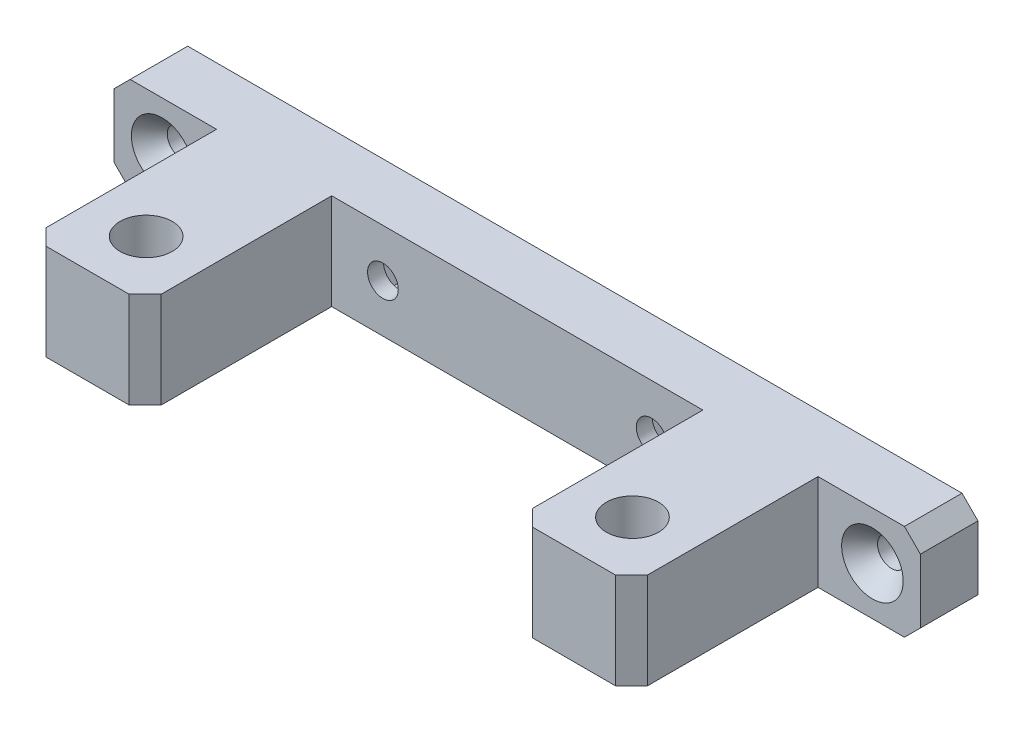
SolidWorks part; units mm, degrees
ref_plane "Front Plane" through (0, 0, 0) normal (0, 0, 1) x (1, 0, 0)
ref_plane "Top Plane" through (0, 0, 0) normal (0, 1, 0) x (1, 0, 0)
ref_plane "Right Plane" through (0, 0, 0) normal (1, 0, 0) x (0, 0, -1)
sketch "Sketch1" plane through (0, 0, 0) normal (0, 0, 1) x (1, 0, 0)
  line L0 (63, 0) -> (63, -15) construction
  line L1 (0, 0) -> (126, 0)
  line L2 (0, 0) -> (0, -15)
  line L3 (0, -15) -> (126, -15)
  line L4 (126, 0) -> (126, -15)
  line L5 (63, -7.5) -> (42, -7.5) construction
  line L6 (42, -7.5) -> (7.5, -7.5) construction
  circle A0 centre (42, -7.5) radius 2.4
  circle A1 centre (7.5, -7.5) radius 2.2
  circle A2 centre (118.5, -7.5) radius 2.2
  circle A3 centre (84, -7.5) radius 2.4
  dimension "D4" = 4.8
  dimension "D6" = 4.4
  dimension "D1" = 15
  dimension "D2" = 126
  dimension "D3" = 21
  dimension "D5" = 34.5
extrude "Boss-Extrude1" add sketch "Sketch1" along normal blind 9
sketch "Sketch2" plane through (0, 0, 9) normal (0, 0, 1) x (1, 0, 0)
  line L0 (63, 0) -> (63, -15) construction
  line L1 (126, 0) -> (0, 0) construction
  line L2 (0, -15) -> (126, -15) construction
  line L3 (63, -7.5) -> (25, -7.5) construction
  line L4 (110, -15) -> (92, -15)
  line L5 (16, 0) -> (34, 0)
  line L6 (16, 0) -> (16, -15)
  line L7 (16, -15) -> (34, -15)
  line L8 (34, 0) -> (34, -15)
  line L9 (16, 0) -> (34, -15) construction
  line L10 (16, -15) -> (34, 0) construction
  line L11 (92, 0) -> (92, -15)
  line L12 (110, 0) -> (92, 0)
  line L13 (110, 0) -> (110, -15)
  dimension "D1" = 29
  dimension "D2" = 18
extrude "Boss-Extrude2" add sketch "Sketch2" along normal blind 29.15
sketch "Sketch4" plane through (0, -15, 0) normal (0, -1, 0) x (1, 0, 0)
  line L0 (16, 9) -> (34, 9) construction
  line L1 (25, 9) -> (25, 29) construction
  line L2 (63, 9) -> (63, 0) construction
  line L3 (34, 9) -> (92, 9) construction
  line L4 (0, 0) -> (126, 0) construction
  line L5 (63, 9) -> (63, 24) construction
  line L6 (63, 24) -> (63, 40) construction
  line L7 (25, 29) -> (25, 40) construction
  circle A0 centre (25, 29) radius 4.075
  circle A1 centre (101, 29) radius 4.075
  dimension "D1" = 8.15
  dimension "D3" = 15
  dimension "D4" = 16
  dimension "D5" = 11
extrude "Cut-Extrude1" cut sketch "Sketch4" against normal through all both and the other way through all
sketch "Sketch5" plane through (0, 0, 0) normal (0, 0, -1) x (-1, 0, 0)
  line L0 (-63, 0) -> (-63, -15) construction
  line L1 (-81.8927, -11.15) -> (-79.7853, -7.5)
  line L2 (-79.7853, -7.5) -> (-81.8927, -3.85)
  line L3 (-81.8927, -3.85) -> (-86.1073, -3.85)
  line L4 (-86.1073, -3.85) -> (-88.2147, -7.5)
  line L5 (-88.2147, -7.5) -> (-86.1073, -11.15)
  line L6 (-86.1073, -11.15) -> (-81.8927, -11.15)
  line L7 (-126, 0) -> (0, 0) construction
  line L8 (0, -15) -> (-126, -15) construction
  line L9 (-39.8927, -11.15) -> (-44.1073, -11.15)
  line L10 (-37.7853, -7.5) -> (-39.8927, -11.15)
  line L11 (-39.8927, -3.85) -> (-37.7853, -7.5)
  line L12 (-44.1073, -3.85) -> (-39.8927, -3.85)
  line L13 (-46.2147, -7.5) -> (-44.1073, -3.85)
  line L14 (-44.1073, -11.15) -> (-46.2147, -7.5)
  circle A0 centre (-84, -7.5) radius 3.65 construction
  dimension "D1" = 7.3
extrude "Cut-Extrude2" cut sketch "Sketch5" against normal blind 6.5
ref_plane "Plane1" through (118.5, 0, 0) normal (1, 0, 0) x (0, 0, -1)
sketch "Sketch7" plane through (118.5, 0, 0) normal (1, 0, 0) x (0, 0, -1)
  line L0 (-9, -7.5) -> (-6, -7.5)
  line L1 (-9, -15) -> (-9, 0) construction
  line L2 (-6, -7.5) -> (-6, -5.3)
  line L3 (-6, -5.3) -> (-9, -2.6921)
  line L4 (-9, -2.6921) -> (-9, -7.5)
  dimension "D1" = 3
  dimension "D2" = 2.2
  dimension "D3" = 131
revolve "Cut-Revolve1" cut sketch "Sketch7" angle 360 about L0
ref_plane "Plane2" through (63, 0, 0) normal (1, 0, 0) x (0, 0, -1)
mirror "Mirror1" about plane through (63, 0, 0) normal (1, 0, 0) of "Cut-Revolve1"
chamfer "Chamfer1" distance 2.5 angle 45 8 edges at (110, -7.5, 38.15) (92, -7.5, 38.15) (34, -7.5, 38.15) (16, -7.5, 38.15) (0, -15, 4.5) (0, 0, 4.5) (126, 0, 4.5) (126, -15, 4.5)
